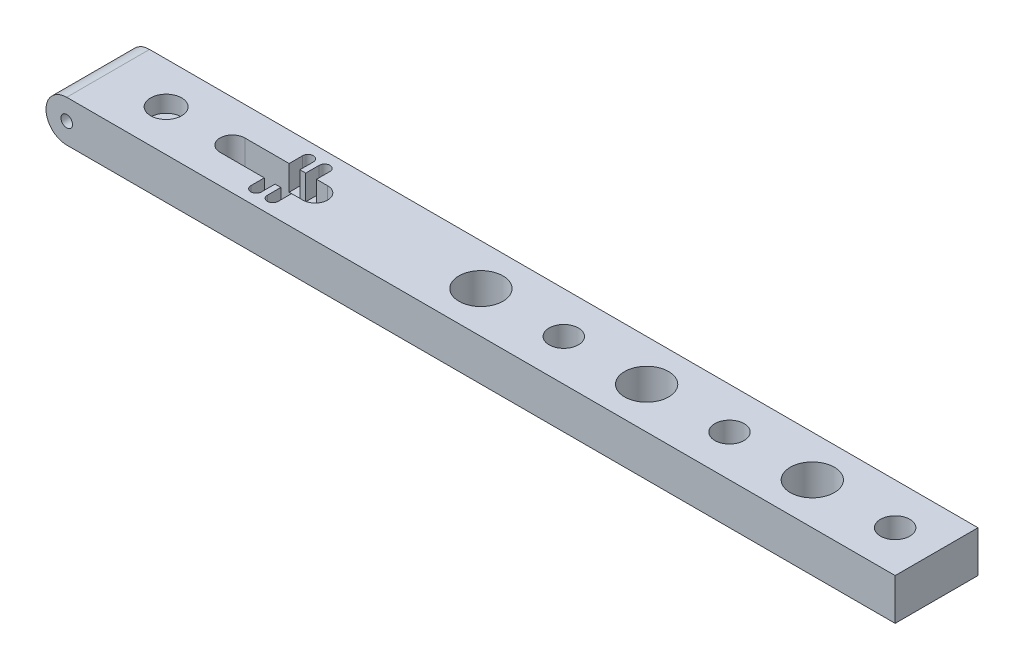
SolidWorks part; units mm, degrees
ref_plane "Front Plane" through (0, 0, 0) normal (0, 0, 1) x (1, 0, 0)
ref_plane "Top Plane" through (0, 0, 0) normal (0, 1, 0) x (1, 0, 0)
ref_plane "Right Plane" through (0, 0, 0) normal (1, 0, 0) x (0, 0, -1)
sketch "Sketch1" plane through (0, 0, 0) normal (0, 0, 1) x (1, 0, 0)
  line L1 (0, 0) -> (127, 0)
  line L3 (0, 6.35) -> (127, 6.35)
  line L4 (127, 0) -> (127, 6.35)
  arc A0 (0, 6.35) -> (0, 0) centre (0, 3.175) ccw
  dimension "D1" = 6.35
extrude "Boss-Extrude1" add sketch "Sketch1" along normal blind 12.7
hole_wizard "#2-56 Tapped Hole1" positions "3DSketch2" profile "Sketch4" tap size "#2-56" standard "ANSI Inch"
sketch3d "3DSketch2"
  line L0 (0, 3.175, 12.7) -> (0, 3.175, 0) construction
  point P0 (0, 3.175, 12.7)
sketch "Sketch4" plane through (0, 3.175, 12.7) normal (1, 0, 0) x (0, -1, 0)
  line L0 (0, 0) -> (0, 3.7092)
  line L1 (0, 3.7092) -> (0.889, 3.175)
  line L2 (0.889, 3.175) -> (0.889, 0)
  line L5 (0.889, 0) -> (0, 0)
  line L10 (0, 3.7092) -> (-0.889, 3.175) construction
  line L11 (0, -6.35) -> (0, 107.95) construction
  dimension "Tap Drill Dia." = 1.778
  dimension "Tap Drill Depth" = 3.175
  dimension "Drill Angle" = 118
cosmetic thread "Hole Thread1" parameters "D1"=3.175, "D2"=2.1844
sketch "Sketch6" plane through (0, 6.35, 0) normal (0, 1, 0) x (1, 0, 0)
  line L0 (19.05, -6.35) -> (31.75, -6.35) construction
  line L1 (19.05, -4.445) -> (31.75, -4.445)
  line L2 (19.05, -8.255) -> (31.75, -8.255)
  line L3 (127, -12.7) -> (0, -12.7) construction
  line L4 (0, -12.7) -> (0, 0) construction
  arc A0 (19.05, -4.445) -> (19.05, -8.255) centre (19.05, -6.35) ccw
  arc A1 (31.75, -8.255) -> (31.75, -4.445) centre (31.75, -6.35) ccw
  point P2 (25.4, -6.35)
  dimension "D4" = 19.05
  dimension "D1" = 3.81
  dimension "D2" = 12.7
  dimension "D3" = 6.35
extrude "Cut-Extrude1" cut sketch "Sketch6" against normal through all
sketch "Sketch7" plane through (0, 6.35, 0) normal (0, 1, 0) x (1, 0, 0)
  line L0 (29.21, -10.3187) -> (29.21, -2.3812) construction
  line L1 (28.3845, -10.3187) -> (28.3845, -2.3812)
  line L2 (30.0355, -10.3187) -> (30.0355, -2.3812)
  line L3 (127, -12.7) -> (0, -12.7) construction
  line L4 (26.67, -10.3187) -> (26.67, -2.3812) construction
  line L5 (25.8445, -10.3187) -> (25.8445, -2.3812)
  line L6 (27.4955, -10.3187) -> (27.4955, -2.3812)
  arc A0 (28.3845, -10.3187) -> (30.0355, -10.3187) centre (29.21, -10.3187) ccw
  arc A1 (30.0355, -2.3812) -> (28.3845, -2.3812) centre (29.21, -2.3812) ccw
  arc A2 (25.8445, -10.3187) -> (27.4955, -10.3187) centre (26.67, -10.3187) ccw
  arc A3 (27.4955, -2.3812) -> (25.8445, -2.3812) centre (26.67, -2.3812) ccw
  point P2 (29.21, -6.35)
  point P12 (26.67, -6.35)
  dimension "D1" = 1.651
  dimension "D2" = 7.9375
  dimension "D3" = 6.35
  dimension "D4" = 10.16
  dimension "D5" = 1.651
  dimension "D6" = 7.9375
  dimension "D7" = 2.54
extrude "Cut-Extrude2" cut sketch "Sketch7" against normal blind 3.81
hole_wizard "#2-56 Tapped Hole2" positions "3DSketch3" profile "Sketch8" tap size "#2-56" standard "ANSI Inch" end condition through all
sketch3d "3DSketch3"
  line L0 (127, 6.35, 12.7) -> (0, 6.35, 12.7) construction
  line L1 (0, 6.35, 12.7) -> (0, 6.35, 0) construction
  point P0 (8.89, 6.35, 6.35)
  dimension "D1" = 6.35
  dimension "D2" = 8.89
cosmetic thread "Hole Thread2" parameters "D2"=2.1844
sketch "Sketch8" plane through (8.89, 6.35, 6.35) normal (1, 0, 0) x (0, 0, 1)
  line L0 (0, 0) -> (0, 6.35)
  line L1 (0, 6.35) -> (0.889, 6.35)
  line L2 (0.889, 6.35) -> (0.889, 0)
  line L5 (0.889, 0) -> (0, 0)
  line L11 (0, -6.35) -> (0, 107.95) construction
  dimension "Thru Tap Drill Dia." = 1.778
  dimension "Thru Tap Drill Depth" = 6.35
hole_wizard "#8 Clearance Hole1" positions "3DSketch4" profile "Sketch9" hole size "#8" standard "ANSI Inch" end condition through all
sketch3d "3DSketch4"
  line L1 (127, 6.35, 12.7) -> (127, 6.35, 0) construction
  line L2 (127, 6.35, 12.7) -> (0, 6.35, 12.7) construction
  point P6 (120.65, 6.35, 6.35)
  dimension "D1" = 6.35
  dimension "D2" = 6.35
sketch "Sketch9" plane through (120.65, 6.35, 6.35) normal (1, 0, 0) x (0, 0, 1)
  line L0 (0, 0) -> (0, 6.35)
  line L1 (0, 6.35) -> (2.2479, 6.35)
  line L2 (2.2479, 6.35) -> (2.2479, 0)
  line L5 (2.2479, 0) -> (0, 0)
  line L11 (0, -6.35) -> (0, 107.95) construction
  dimension "Thru Hole Dia." = 4.4958
  dimension "Thru Hole Depth" = 6.35
hole_wizard "1/4 Clearance Hole1" positions "3DSketch5" profile "Sketch10" hole size "1/4" standard "ANSI Inch" end condition through all
sketch3d "3DSketch5"
  line L0 (127, 6.35, 12.7) -> (0, 6.35, 12.7) construction
  line L1 (127, 6.35, 12.7) -> (127, 6.35, 0) construction
  point P0 (107.95, 6.35, 6.35)
  dimension "D1" = 6.35
  dimension "D2" = 19.05
sketch "Sketch10" plane through (107.95, 6.35, 6.35) normal (1, 0, 0) x (0, 0, 1)
  line L0 (0, 0) -> (0, 6.35)
  line L1 (0, 6.35) -> (3.3782, 6.35)
  line L2 (3.3782, 6.35) -> (3.3782, 0)
  line L5 (3.3782, 0) -> (0, 0)
  line L11 (0, -6.35) -> (0, 107.95) construction
  dimension "Thru Hole Dia." = 6.7564
  dimension "Thru Hole Depth" = 6.35
pattern_linear "LPattern1" count 3 spacing 25.4 along (-1, 0, 0) of "#8 Clearance Hole1", "1/4 Clearance Hole1"
sketch "Sketch11" plane through (0, 6.35, 0) normal (0, 1, 0) x (1, 0, 0)
  circle A0 centre (8.89, -6.35) radius 2.3813
  dimension "D1" = 4.7625
extrude "Cut-Extrude3" cut sketch "Sketch11" against normal blind 2.54
